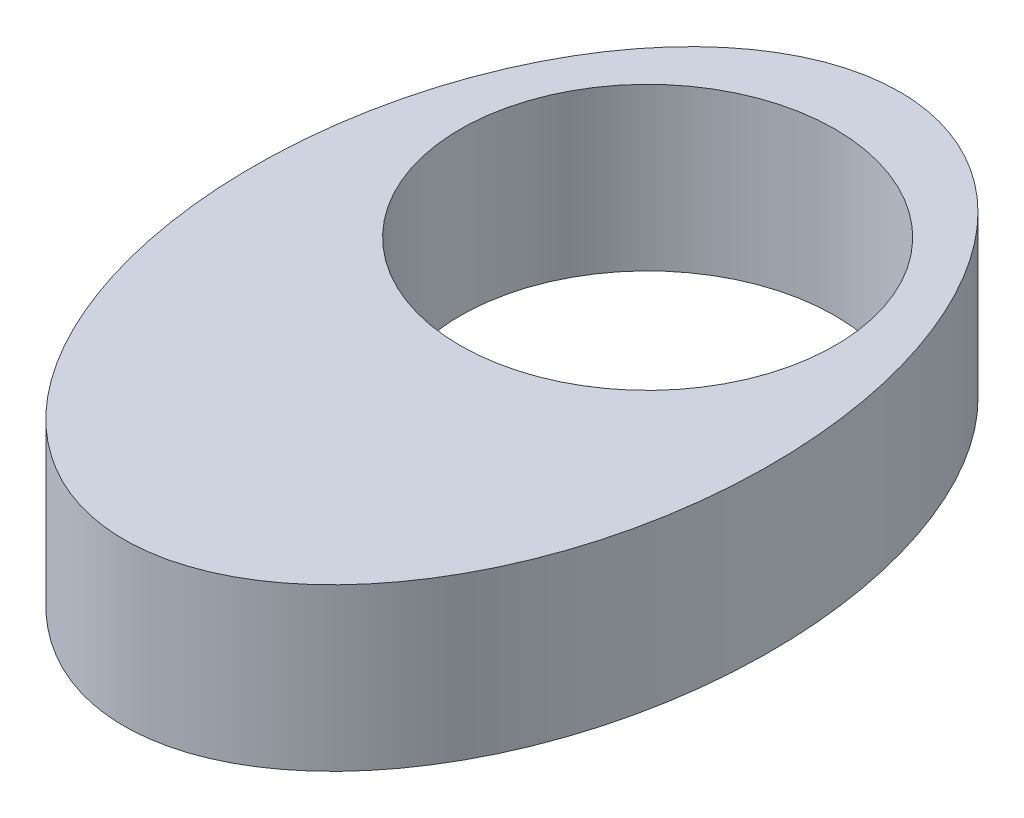
SolidWorks part; units mm, degrees
ref_plane "Front Plane" through (0, 0, 0) normal (0, 0, 1) x (1, 0, 0)
ref_plane "Top Plane" through (0, 0, 0) normal (0, 1, 0) x (1, 0, 0)
ref_plane "Right Plane" through (0, 0, 0) normal (1, 0, 0) x (0, 0, -1)
sketch "Sketch1" plane through (0, 0, 0) normal (0, 1, 0) x (1, 0, 0)
  circle A0 centre (0, 21) radius 29
  ellipse E0 centre (0, 0) end of major axis (0, 60) minor radius 40
  ellipse E1 centre (0, 0) end of major axis (0, 55) minor radius 35
  dimension "D7" = 58
  dimension "D1" = 120
  dimension "D2" = 80
  dimension "D3" = 110
  dimension "D4" = 70
  dimension "D5" = 35
  dimension "D6" = 40
  dimension "D8" = 21
  dimension "D9" = 35
extrude "Boss-Extrude1" add sketch "Sketch1" along normal blind 25 contours E1 A0 | E0 E1
